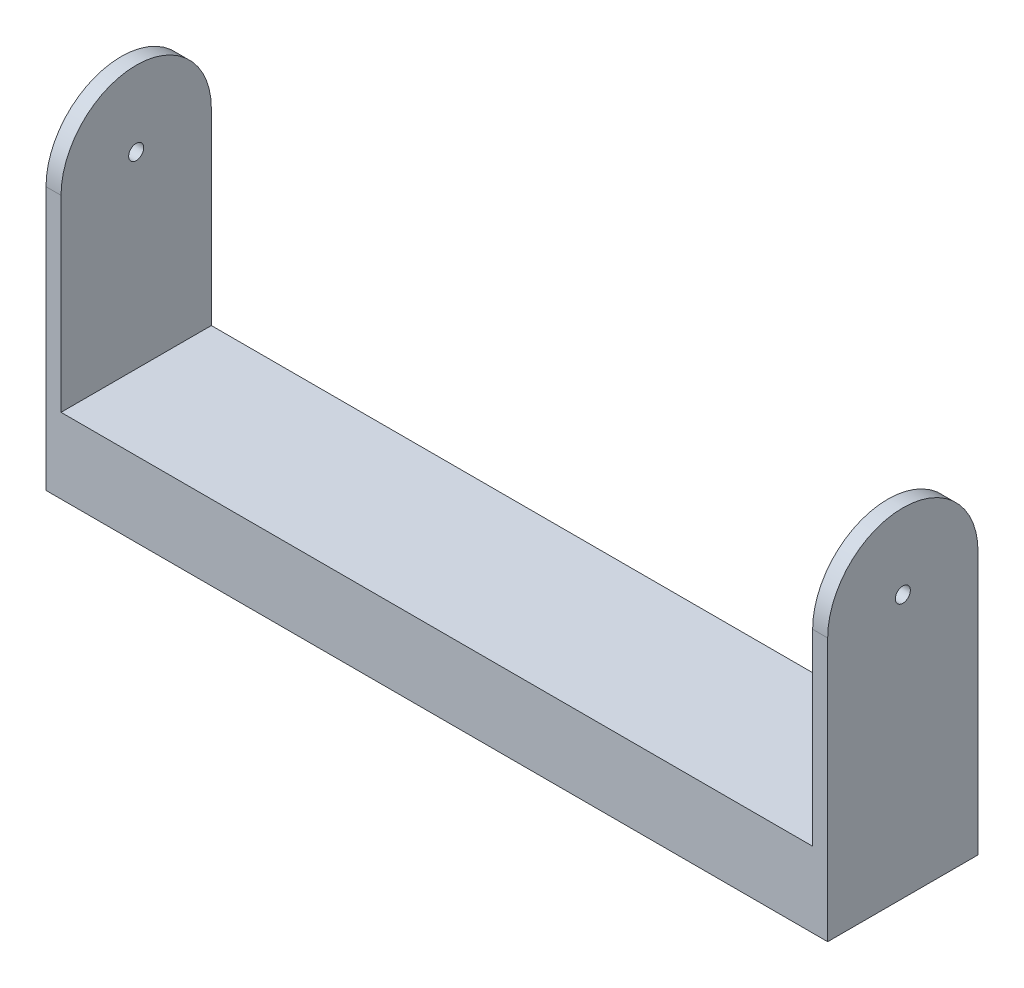
SolidWorks part; units mm, degrees
ref_plane "Front Plane" through (0, 0, 0) normal (0, 0, 1) x (1, 0, 0)
ref_plane "Top Plane" through (0, 0, 0) normal (0, 1, 0) x (1, 0, 0)
ref_plane "Right Plane" through (0, 0, 0) normal (1, 0, 0) x (0, 0, -1)
sketch "Sketch1" plane through (0, 0, 0) normal (0, 0, 1) x (1, 0, 0)
  line L1 (0, 0) -> (1040, 0)
  line L2 (0, 0) -> (0, -100)
  line L3 (0, -100) -> (1040, -100)
  line L4 (1040, 0) -> (1040, -100)
  dimension "D1" = 1040
  dimension "D2" = 100
extrude "Boss-Extrude1" add sketch "Sketch1" along normal blind 200
sketch "Sketch2" plane through (1040, 0, 0) normal (1, 0, 0) x (0, 0, -1)
  line L2 (-200, 0) -> (-200, 250)
  line L3 (0, 250) -> (0, 0)
  line L4 (0, 250) -> (-100, 250) construction
  line L5 (-100, 250) -> (-200, 250) construction
  line L6 (0, 0) -> (-200, 0)
  arc A1 (-200, 250) -> (0, 250) centre (-100, 250) cw
  dimension "D1" = 250
ref_plane "Plane1" through (520, 0, 0) normal (1, 0, 0) x (0, 0, -1)
extrude "Boss-Extrude3" add sketch "Sketch2" against normal blind 20
mirror "Mirror2" about plane through (520, 0, 0) normal (1, 0, 0) of "Boss-Extrude3"
sketch "Sketch3" plane through (20, 0, 0) normal (1, 0, 0) x (0, 0, -1)
  circle A0 centre (-100, 250) radius 10
  arc A1 (0, 250) -> (-200, 250) centre (-100, 250) ccw construction
  point P6 (-100, 350)
  dimension "D1" = 20
extrude "Cut-Extrude1" cut sketch "Sketch3" against normal through all both and the other way through all contours A0
sketch "Sketch4" plane through (520, 0, 0) normal (1, 0, 0) x (0, 0, -1)
